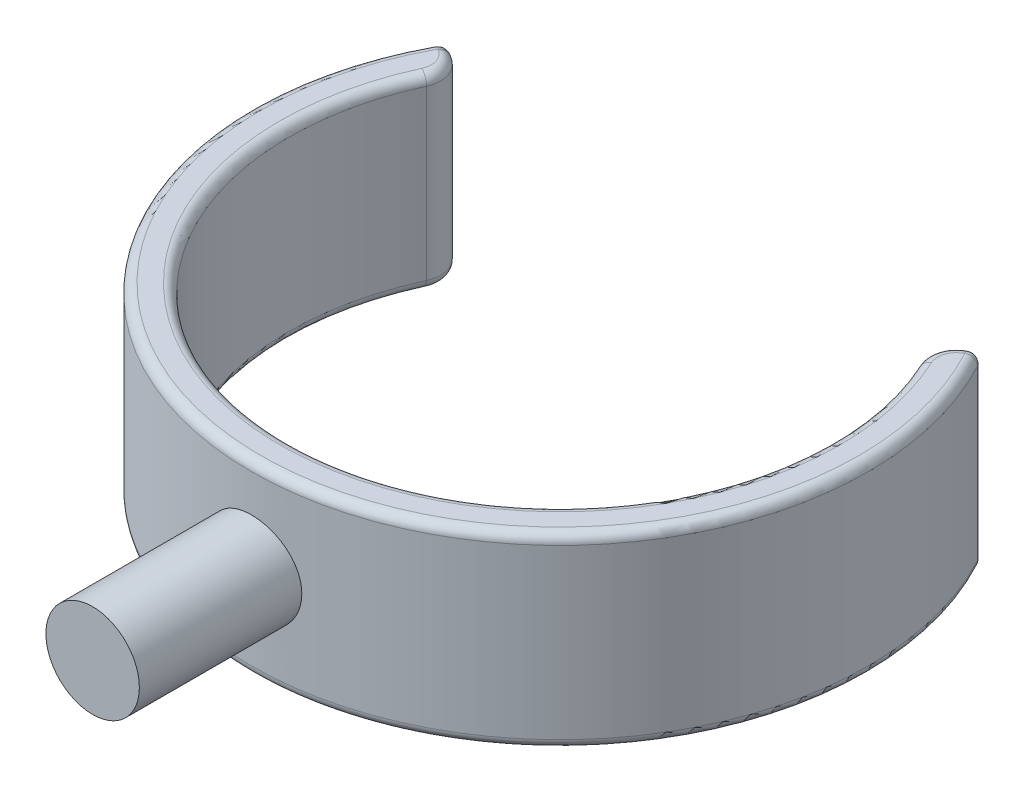
SolidWorks part; units mm, degrees
ref_plane "Alzado" through (0, 0, 0) normal (0, 0, 1) x (1, 0, 0)
ref_plane "Planta" through (0, 0, 0) normal (0, 1, 0) x (1, 0, 0)
ref_plane "Vista lateral" through (0, 0, 0) normal (1, 0, 0) x (0, 0, -1)
sketch "Croquis1" plane through (0, 0, 0) normal (0, 1, 0) x (1, 0, 0)
  line L0 (0, 0) -> (0, 40) construction
  line L1 (0, 0) -> (28.5788, 16.5)
  line L2 (0, 0) -> (-28.5788, 16.5)
  arc A0 (-28.5788, 16.5) -> (28.5788, 16.5) centre (0, 0) ccw
  arc A1 (-25.1147, 14.5) -> (25.1147, 14.5) centre (0, 0) ccw
  circle A3 centre (0, 0) radius 29 construction
  circle A4 centre (0, 0) radius 33 construction
  point P3 (38.2522, 11.6949)
  point P8 (37, 0)
  dimension "D1" = 66
  dimension "D3" = 60
  dimension "D2" = 4
extrude "Extruir1" add sketch "Croquis1" along normal blind 20 contours A1 L2 A0 L1
sketch "Croquis2" plane through (0, 0, 0) normal (0, 0, 1) x (1, 0, 0)
  line L0 (0, 0) -> (0, 20) construction
  line L1 (33, 20) -> (-33, 20) construction
  circle A0 centre (0, 10) radius 5
  dimension "D1" = 10
extrude "Extruir2" add sketch "Croquis2" against normal up to surface (17.381 mm away) from offset 50
fillet "Redondeo1" radius 3 2 edges at (-25.1147, 10, -14.5) (25.1147, 10, -14.5)
fillet "Redondeo2" radius 1 14 edges at (0, 0, 33) (28.0848, 0, -16.2148) (26.2326, 0, -14.243) (0, 0, 29) (-26.2326, 0, -14.243) (-28.0848, 0, -16.2148) (26.2326, 20, -14.243) (28.0848, 20, -16.2148) (0, 20, 33) (-28.0848, 20, -16.2148) (-26.2326, 20, -14.243) (0, 20, 29) (28.5788, 10, -16.5) (-28.5788, 10, -16.5)
